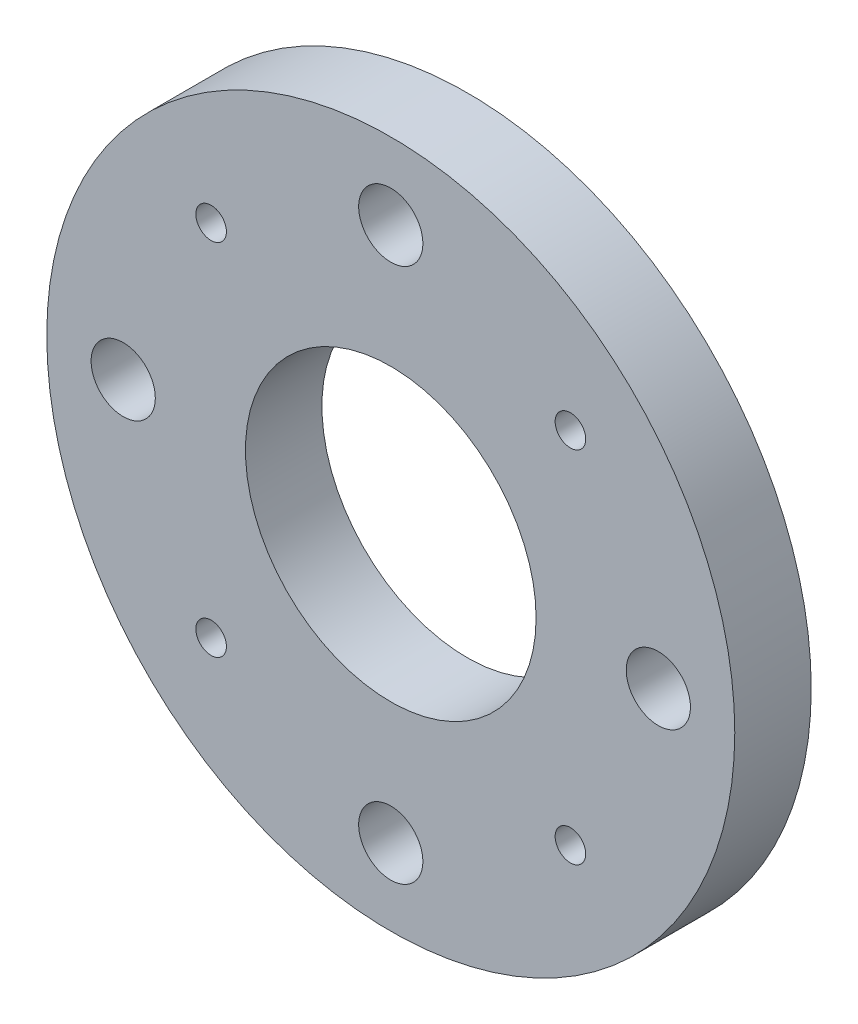
SolidWorks part; units mm, degrees
ref_plane "前视基准面" through (0, 0, 0) normal (0, 0, 1) x (1, 0, 0)
ref_plane "上视基准面" through (0, 0, 0) normal (0, 1, 0) x (1, 0, 0)
ref_plane "右视基准面" through (0, 0, 0) normal (1, 0, 0) x (0, 0, -1)
sketch "草图1" plane through (0, 0, 0) normal (0, 0, 1) x (1, 0, 0)
  line L3 (0, -1000) -> (0, 49000) construction
  circle A0 centre (0, 0) radius 19.01
  circle A1 centre (0, 0) radius 45
  dimension "D5" = 38.02
  dimension "D1" = 90
extrude "拉伸1" add sketch "草图1" along normal blind 10
sketch "草图2" plane through (0, 0, 10) normal (0, 0, 1) x (1, 0, 0)
  line L0 (0, -1000) -> (0, 49000) construction
  line L1 (-1000, 0) -> (49000, 0) construction
  line L2 (-707.0853, -707.0853) -> (34648.2538, 34648.2538) construction
  line L3 (708.507, -708.507) -> (-34646.832, 34646.832) construction
  line L4 (-23.5, 23.5) -> (23.5, 23.5) construction
  line L5 (23.5, 23.5) -> (23.5, -23.5) construction
  line L6 (23.5, -23.5) -> (-23.5, -23.5) construction
  line L7 (-23.5, -23.5) -> (-23.5, 23.5) construction
  circle A0 centre (0, 0) radius 35 construction
  dimension "D1" = 70
  dimension "D2" = 47
  dimension "D3" = 47
hole_wizard "M4 螺纹孔1" positions "3D草图1" profile "草图3" tap size "M4" standard "ISO"
sketch3d "3D草图1"
  point P0 (-23.5, 23.5, 10)
  point P3 (23.5, 23.5, 10)
  point P6 (23.5, -23.5, 10)
  point P9 (-23.5, -23.5, 10)
sketch "草图3" plane through (-23.5, 23.5, 10) normal (1, 0, 0) x (0, -1, 0)
  line L0 (0, 0) -> (0, 11.0914)
  line L1 (0, 11.0914) -> (1.65, 10.1)
  line L2 (1.65, 10.1) -> (1.65, 8)
  line L3 (1.65, 8) -> (2, 8)
  line L4 (2, 8) -> (2, 0)
  line L5 (2, 0) -> (0, 0)
  line L10 (0, 11.0914) -> (-1.65, 10.1) construction
  line L11 (0, -6.35) -> (0, 107.95) construction
  dimension "蹟恇謂郰芛眻噤" = 3.3
  dimension "蹟恇謂郰芛旮僅" = 10.1
  dimension "蹟恇翋眻噤" = 4
  dimension "蹟恇旮僅" = 8
  dimension "絳芛褒僅" = 118
sketch "草图4" plane through (0, 0, 10) normal (0, 0, 1) x (1, 0, 0)
  line L0 (0, -201000) -> (0, 249000) construction
  line L1 (-201000, 0) -> (249000, 0) construction
  circle A0 centre (0, 35) radius 4.2
  circle A1 centre (0, 0) radius 35 construction
  circle A2 centre (-35, 0) radius 4.2
  circle A3 centre (0, -35) radius 4.2
  circle A4 centre (35, 0) radius 4.2
  dimension "D1" = 8.4
extrude "切除-拉伸1" cut sketch "草图4" against normal blind 10
